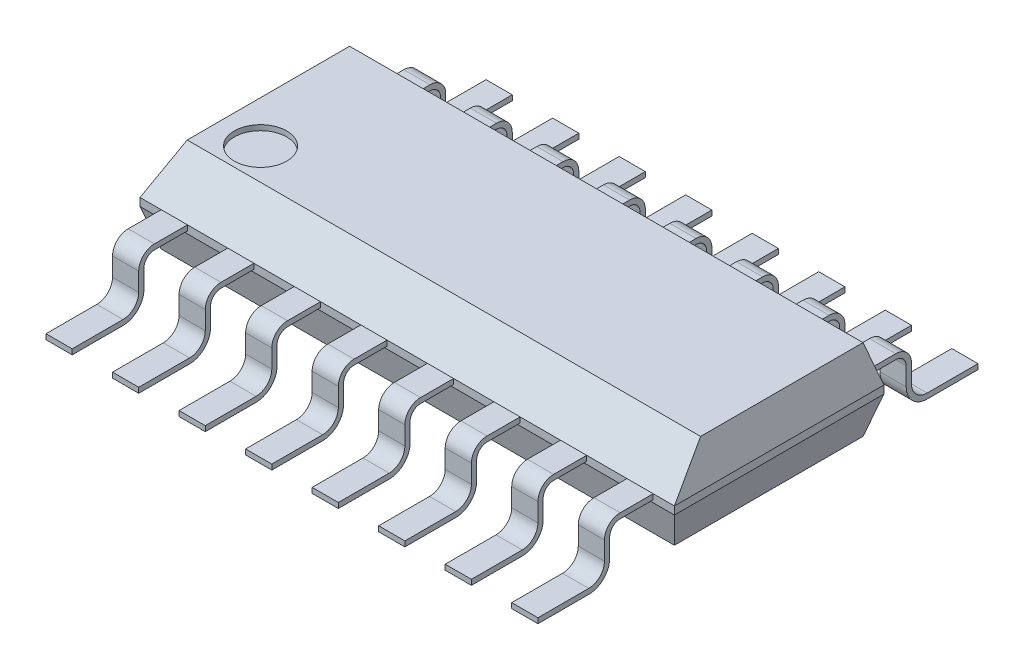
SolidWorks part; units mm, degrees
ref_plane "Спереди" through (0, 0, 0) normal (0, 0, 1) x (1, 0, 0)
ref_plane "Сверху" through (0, 0, 0) normal (0, 1, 0) x (1, 0, 0)
ref_plane "Справа" through (0, 0, 0) normal (1, 0, 0) x (0, 0, -1)
sketch "Эскиз1" plane through (0, 0, 0) normal (0, 1, 0) x (1, 0, 0)
  line L1 (-5.1, -2) -> (5.1, -2)
  line L2 (-5.1, -2) -> (-5.1, 2)
  line L3 (-5.1, 2) -> (5.1, 2)
  line L4 (5.1, -2) -> (5.1, 2)
  line L5 (-5.1, -2) -> (5.1, 2) construction
  line L6 (-5.1, 2) -> (5.1, -2) construction
  point P0 (0, 0)
  dimension "D1" = 10.2
  dimension "D2" = 4
extrude "Бобышка-Вытянуть1" add sketch "Эскиз1" along normal mid plane 1.55
sketch "Эскиз2" plane through (0, 0.775, 0) normal (0, 1, 0) x (1, 0, 0)
  line L0 (-5.1, 2) -> (-5.1, -2) construction
  circle A0 centre (-4.1, -0.7) radius 0.5
  dimension "D1" = 1
  dimension "D2" = 0.7
  dimension "D3" = 1
extrude "Вырез-Вытянуть1" cut sketch "Эскиз2" against normal blind 0.1
chamfer "Фаска1" distance 0.2 distance2 0.7 2 edges at (0, -0.775, -2) (0, -0.775, 2)
chamfer "Фаска2" distance 0.7 distance2 0.2 1 edges at (0, 0.775, -2)
chamfer "Фаска3" distance 0.7 angle 45 1 edges at (0, 0.775, 2)
sketch "Эскиз3" plane through (0, 0, 0) normal (0, 0, 1) x (1, 0, 0)
  line L0 (-5.1, 0.075) -> (-4.9, 0.775)
  line L1 (-5.1, 0.775) -> (5.1, 0.775) construction
  line L2 (-4.9, 0.775) -> (-5.1, 0.775)
  line L3 (-5.1, 0.775) -> (-5.1, 0.075)
  line L4 (-5.1, -0.075) -> (-4.9, -0.775)
  line L5 (5.1, -0.775) -> (-5.1, -0.775) construction
  line L6 (-4.9, -0.775) -> (-5.1, -0.775)
  line L7 (-5.1, -0.775) -> (-5.1, -0.075)
  line L8 (0, 0) -> (0, 1.4474) construction
  line L9 (5.1, -0.775) -> (5.1, -0.075)
  line L10 (4.9, -0.775) -> (5.1, -0.775)
  line L11 (5.1, -0.075) -> (4.9, -0.775)
  line L12 (5.1, 0.775) -> (5.1, 0.075)
  line L13 (4.9, 0.775) -> (5.1, 0.775)
  line L14 (5.1, 0.075) -> (4.9, 0.775)
  dimension "D1" = 0.2
extrude "Вырез-Вытянуть2" cut sketch "Эскиз3" against normal through all both and the other way through all
sketch "Эскиз4" plane through (0, 0, 0) normal (1, 0, 0) x (0, 0, -1)
  line L0 (-2, 0.075) -> (-2.63, 0.075)
  line L1 (-2.93, -0.225) -> (-2.93, -0.575)
  line L2 (-3.23, -0.875) -> (-4.2, -0.875)
  line L3 (1.8, 0.775) -> (-1.3, 0.775) construction
  line L4 (-2, -0.025) -> (-2.63, -0.025)
  line L5 (-2.83, -0.225) -> (-2.83, -0.575)
  line L6 (-3.23, -0.975) -> (-4.2, -0.975)
  line L7 (-4.2, -0.975) -> (-4.2, -0.875)
  line L8 (-2, -0.025) -> (-2, 0.075)
  arc A0 (-2.93, -0.575) -> (-3.23, -0.875) centre (-3.23, -0.575) cw
  arc A1 (-2.63, 0.075) -> (-2.93, -0.225) centre (-2.63, -0.225) ccw
  arc A2 (-2.63, -0.025) -> (-2.83, -0.225) centre (-2.63, -0.225) ccw
  arc A3 (-2.83, -0.575) -> (-3.23, -0.975) centre (-3.23, -0.575) cw
  point P9 (-2.93, -0.875)
  point P12 (-2.93, 0.075)
  dimension "D4" = 0.3
  dimension "D1" = 1.27
  dimension "D2" = 0.93
  dimension "D3" = 1.65
  dimension "D5" = 0.1
extrude "Бобышка-Вытянуть2" add sketch "Эскиз4" along normal mid plane 0.5 from offset 0.635 separate body
pattern_linear "Линейный массив1" count 4 spacing 1.27 along (1, 0, 0) of bodies 106
mirror "Зеркальное отражение1" about plane through (0, 0, 0) normal (1, 0, 0) of bodies 106 107 108 109
mirror "Зеркальное отражение2" about plane through (0, 0, 0) normal (0, 0, 1) of bodies 106 107 108 109 110 111 112 113
